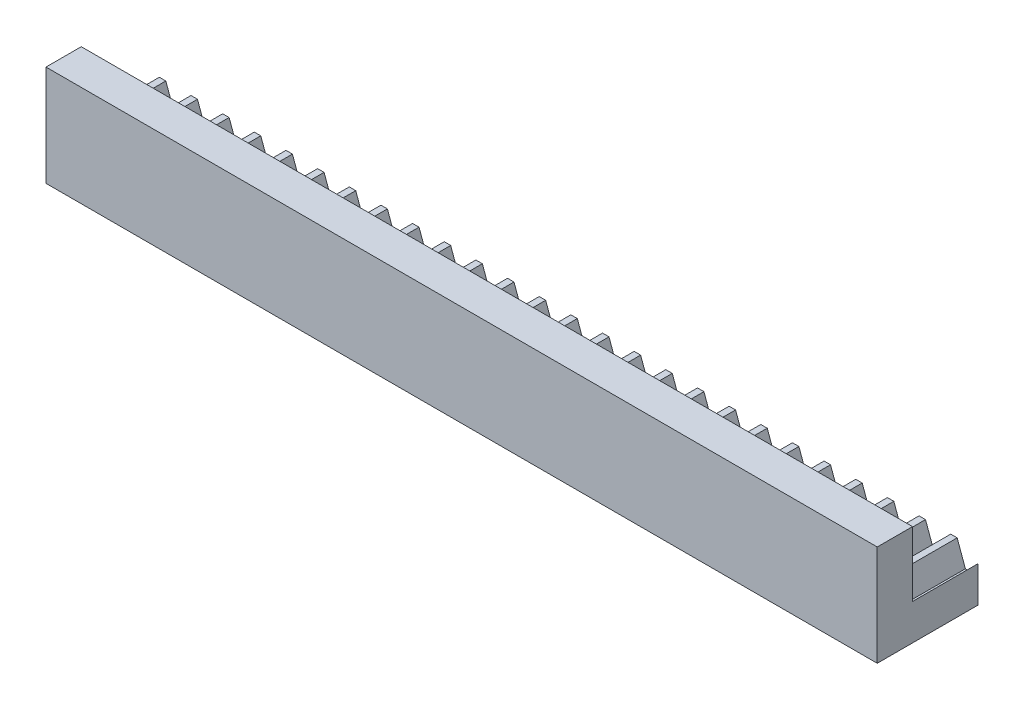
SolidWorks part; units mm, degrees
extrude "Blank" add sketch "BlankSke" against normal blind 13
sketch "BlankSke" plane through (0, 0, 0) normal (0, 0, 1) x (1, 0, 0)
  line L1 (0, 0) -> (165, 0)
  line L2 (0, 0) -> (0, 9.5)
  line L3 (0, 9.5) -> (165, 9.5)
  line L4 (165, 0) -> (165, 9.5)
  dimension "Length" = 165
  dimension "Blank_height" = 9.5
ref_plane "Plane1" through (0, 0, 0) normal (0, 0, 1) x (1, 0, 0)
ref_plane "Plane2" through (0, 0, 0) normal (0, 1, 0) x (1, 0, 0)
ref_plane "Plane3" through (0, 0, 0) normal (1, 0, 0) x (0, 0, -1)
sketch "HoldingSke" plane through (0, 0, 0) normal (0, 1, 0) x (1, 0, 0)
  line L0 (0, 0) -> (0.0696, 0.4951)
  line L1 (-15, 0) -> (100, 0) construction
  line L2 (0, 0) -> (-2.1039, 2.3779)
  line L3 (0, 0) -> (-11.863, 4.5341)
  line L4 (0, 0) -> (7.6251, 4.0543)
  line L5 (0, 0) -> (-23.7986, -8.8762)
  line L6 (0, 0) -> (-10.5278, -7.1032)
  line L9 (-71.009, 38.7566) -> (84.0403, 95.1899)
  line L10 (-76.2, 4.3779) -> (-68.7, 4.3779)
  line L11 (0, 0) -> (-13, 0)
  line L12 (-76.2, 101.6) -> (-76.133, 101.6)
  line L13 (24.9733, 27.94) -> (52.9518, 28.4284)
  line L14 (24.9733, 27.94) -> (24.9743, 27.94)
  line L15 (24.9733, 27.94) -> (100.4006, 29.5858)
  circle A0 centre (0, 0) radius 19.05
  circle A1 centre (0, 0) radius 3.75
  circle A2 centre (0, 0) radius 12.7
  dimension "MPH" = 7.5
  dimension "Diameter" = 38.1
  dimension "Num_teeth" = 28
  dimension "Pitch" = 0.5
  dimension "Show_teeth" = 998
  dimension "Thickness" = 12.7
  dimension "Ap" = 20
  dimension "Pitch_height" = 7.5
  dimension "Width" = 13
  dimension "Backlash" = 0.067
  dimension "Addendum_fac" = 1
  dimension "Dedendum_fac" = 1.25
  dimension "Clearance_fac" = 0.25
  dimension "Dedendum_add" = 0.001
  dimension "Length" = 165
  dimension "Module" = 2
sketch "TooCutSkeIll" plane through (0, 0, 0) normal (0, 0, 1) x (1, 0, 0)
  line L0 (-2.4806, 9.4474) -> (-0.9819, 5.3296)
  line L1 (-0.5111, 5) -> (0.5111, 5)
  line L2 (0.9819, 5.3296) -> (2.4806, 9.4474)
  line L3 (165, 9.5) -> (0, 9.5) construction
  line L4 (0, 0) -> (0, 64.897) construction
  line L5 (-13.208, 7.5) -> (12.954, 7.5) construction
  line L6 (0, 0) -> (165, 0) construction
  line L7 (1.7718, 7.5) -> (1.7718, 48.7463) construction
  line L8 (-1.7718, 7.5) -> (-1.7718, 48.7463) construction
  line L9 (2.5558, 9.5) -> (2.5558, 9.5254)
  line L10 (-2.5558, 9.5) -> (-2.5558, 9.5254)
  line L11 (-2.5558, 9.5254) -> (2.5558, 9.5254)
  arc A0 (0.5111, 5) -> (0.9819, 5.3296) centre (0.5111, 5.501) ccw
  arc A1 (-0.9819, 5.3296) -> (-0.5111, 5) centre (-0.5111, 5.501) ccw
  arc A2 (2.5558, 9.5) -> (2.4806, 9.4474) centre (2.5558, 9.42) ccw
  arc A3 (-2.4806, 9.4474) -> (-2.5558, 9.5) centre (-2.5558, 9.42) ccw
  dimension "Pitch_height" = 7.5
  dimension "Addendum_plus" = 2.0254
  dimension "Pressure_angle" = 20
  dimension "Gap_width" = 3.5436
  dimension "Dedendum" = 2.5
extrude "ToothCutIll" [suppressed] cut sketch "TooCutSkeIll" against normal through all
sketch "TooCutSkeSim" plane through (0, 0, 0) normal (0, 0, 1) x (1, 0, 0)
  line L0 (0.8619, 5) -> (-0.8619, 5)
  line L1 (2.509, 9.5254) -> (0.8619, 5)
  line L2 (0, 17.4625) -> (0, 53.467) construction
  line L3 (2.509, 9.5254) -> (-2.509, 9.5254)
  line L6 (-2.509, 9.5254) -> (-0.8619, 5)
  line L9 (-1.7718, 7.5) -> (1.7718, 7.5) construction
  line L10 (0, 0) -> (165, 0) construction
  line L11 (1.7718, 7.5) -> (1.7718, 53.467) construction
  line L12 (-1.7718, 7.5) -> (-1.7718, 53.467) construction
  dimension "Pitch_height" = 7.5
  dimension "Addendum_plus" = 2.0254
  dimension "Pressure_angle" = 20
  dimension "Gap_width" = 3.5436
  dimension "Dedendum" = 2.5
extrude "ToothCutSim" cut sketch "TooCutSkeSim" against normal through all
pattern_linear "TeethCuts" count 27 spacing 6.2832 along (1, 0, 0) of "ToothCutIll", "ToothCutSim"
sketch "Esquisse1" plane through (0, 0, 0) normal (0, 0, 1) x (1, 0, 0)
  line L1 (0, 0) -> (165, 0)
  line L2 (0, 0) -> (0, 20)
  line L3 (0, 20) -> (165, 20)
  line L4 (165, 0) -> (165, 20)
  dimension "D1" = 165
  dimension "D2" = 20
extrude "Boss.-Extru.1" add sketch "Esquisse1" along normal blind 7
equation "' \"Module@HoldingSke\" = 6.35"
equation "' \"Num_teeth@HoldingSke\" = 12"
equation "' \"Ap@HoldingSke\" =  20"
equation "' \"Ap@HoldingSke\" = 20"
equation "' \"Width@HoldingSke\" = 0.25 * 25.4"
equation "' \"Show_teeth@HoldingSke\" = 500"
equation "' \"Backlash@HoldingSke\" = 0.009 * 25.4"
equation "' \"Addendum_fac@HoldingSke\" = 1.0"
equation "' \"Dedendum_fac@HoldingSke\" = 1.25"
equation "' \"Dedendum_add@HoldingSke\" = 0.00005 * 25.4"
equation "' \"Clearance_fac@HoldingSke\" = 0.25"
equation "' \"Pitch_height@HoldingSke\" = 1 * 25.4"
equation "' \"Length@HoldingSke\" = 4.71 * 25.4"
equation "\"Pitch@HoldingSke\" = 1 / \"Module@HoldingSke\""
equation "\"MPH@HoldingSke\" = \"Dedendum_fac@HoldingSke\" / \"Pitch@HoldingSke\" + 2 * \"Dedendum_add@HoldingSke\" + 0.002 * 25.4"
equation "\"MPH@HoldingSke\" = ((sgn( \"MPH@HoldingSke\" - \"Pitch_height@HoldingSke\")+1)*( \"MPH@HoldingSke\" - \"Pitch_height@HoldingSke\"))/2 + \"Pitch_height@HoldingSke\""
equation "\"Blank_height@BlankSke\" = \"Pitch_height@HoldingSke\" + \"Addendum_fac@HoldingSke\"  / \"Pitch@HoldingSke\" "
equation "\"Length@BlankSke\" =  \"Length@HoldingSke\""
equation "\"Face_width@Blank\" = \"Width@HoldingSke\""
equation "\"Pressure_angle@TooCutSkeIll\" = \"Ap@HoldingSke\""
equation "\"Addendum_plus@TooCutSkeIll\" =  \"Addendum_fac@HoldingSke\"  / \"Pitch@HoldingSke\" + 0.001 *25.4"
equation "\"Dedendum@TooCutSkeIll\" = \"Dedendum_fac@HoldingSke\"  / \"Pitch@HoldingSke\""
equation "\"Pitch_height@TooCutSkeIll\" =  \"MPH@HoldingSke\""
equation "\"Gap_width@TooCutSkeIll\" = 3.14159265 / 2 / \"Pitch@HoldingSke\" + 6 * \"Backlash@HoldingSke\""
equation "\"Pressure_angle@TooCutSkeSim\" = \"Ap@HoldingSke\""
equation "\"Addendum_plus@TooCutSkeSim\" =  \"Addendum_fac@HoldingSke\"  / \"Pitch@HoldingSke\" + 0.001 * 25.4"
equation "\"Dedendum@TooCutSkeSim\" = \"Dedendum_fac@HoldingSke\"  / \"Pitch@HoldingSke\""
equation "\"Pitch_height@TooCutSkeSim\" =  \"MPH@HoldingSke\""
equation "\"Gap_width@TooCutSkeSim\" = 3.14159265 / 2 / \"Pitch@HoldingSke\" + 6 * \"Backlash@HoldingSke\""
equation "\"Root_fillet@TooCutSkeIll\" = \"Clearance_fac@HoldingSke\" / \"Pitch@HoldingSke\" + \"Dedendum_add@HoldingSke\""
equation "\"Break_rad@TooCutSkeIll\" = 0.02 / \"Pitch@HoldingSke\" * 2"
equation "\"Linear_pitch@TeethCuts\" = 3.14159265 / \"Pitch@HoldingSke\""
equation "\"Num_teeth@HoldingSke\" = int( ( \"Length@HoldingSke\" + 0 ) / (3.14159265 / \"Pitch@HoldingSke\")) + 0.9999  + 1"
equation " \"Num_teeth@TeethCuts\" = int( \"Show_teeth@HoldingSke\" ) + 1"
equation " \"Num_teeth@TeethCuts\" = ((sgn( \"Num_teeth@TeethCuts\" - \"Num_teeth@HoldingSke\" )-1)*( \"Num_teeth@TeethCuts\" - \"Num_teeth@HoldingSke\" ))/-2+ \"Num_teeth@HoldingSke\""
equation " \"Num_teeth@TeethCuts\" = ((sgn( \"Num_teeth@TeethCuts\" - 2.0)+1)*( \"Num_teeth@TeethCuts\" - 2.0))/2 +2.0"
